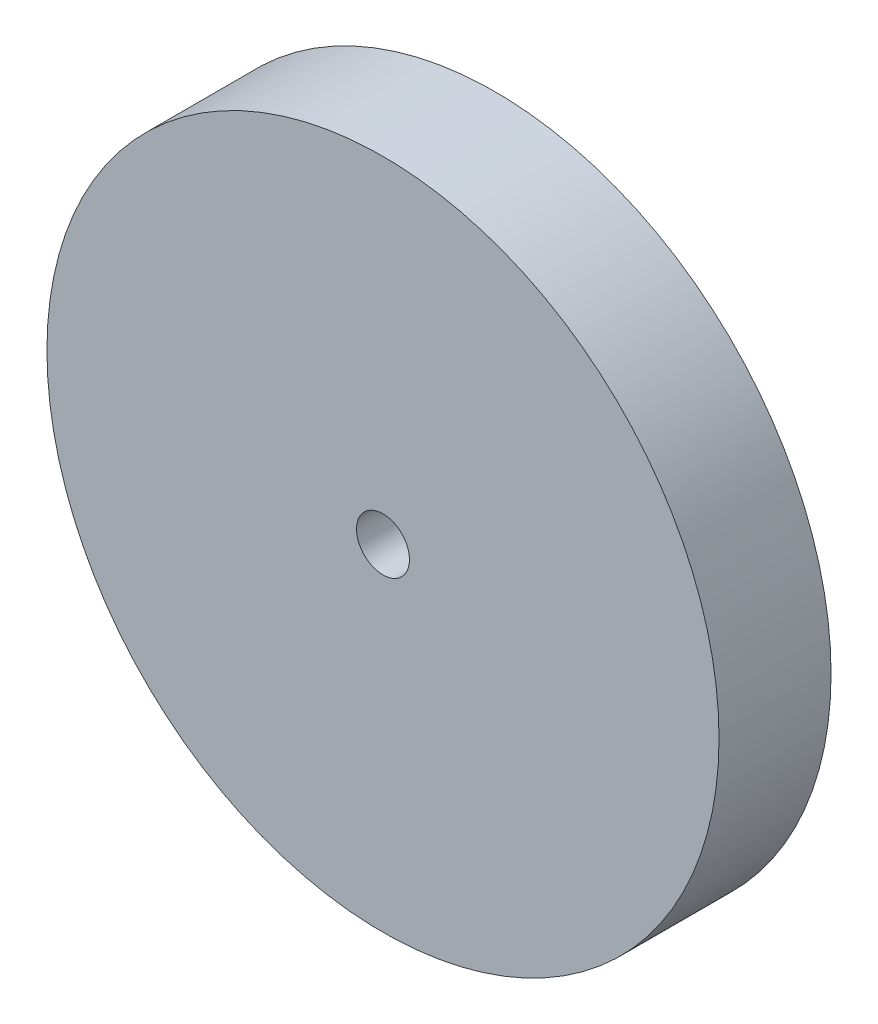
SolidWorks part; units mm, degrees
ref_plane "Front Plane" through (0, 0, 0) normal (0, 0, 1) x (1, 0, 0)
ref_plane "Top Plane" through (0, 0, 0) normal (0, 1, 0) x (1, 0, 0)
ref_plane "Right Plane" through (0, 0, 0) normal (1, 0, 0) x (0, 0, -1)
sketch "Sketch1" plane through (0, 0, 0) normal (0, 0, 1) x (1, 0, 0)
  circle A0 centre (0, 0) radius 38.1
  circle A1 centre (0, 0) radius 3
  dimension "D1" = 76.2
  dimension "D2" = 6
extrude "Boss-Extrude1" add sketch "Sketch1" along normal blind 12.7
sketch "Sketch2" plane through (0, 0, 0) normal (0, 0, -1) x (-1, 0, 0)
  circle A0 centre (0, 0) radius 7.9375
  dimension "D1" = 15.875
extrude "Cut-Extrude1" cut sketch "Sketch2" against normal blind 5.08
